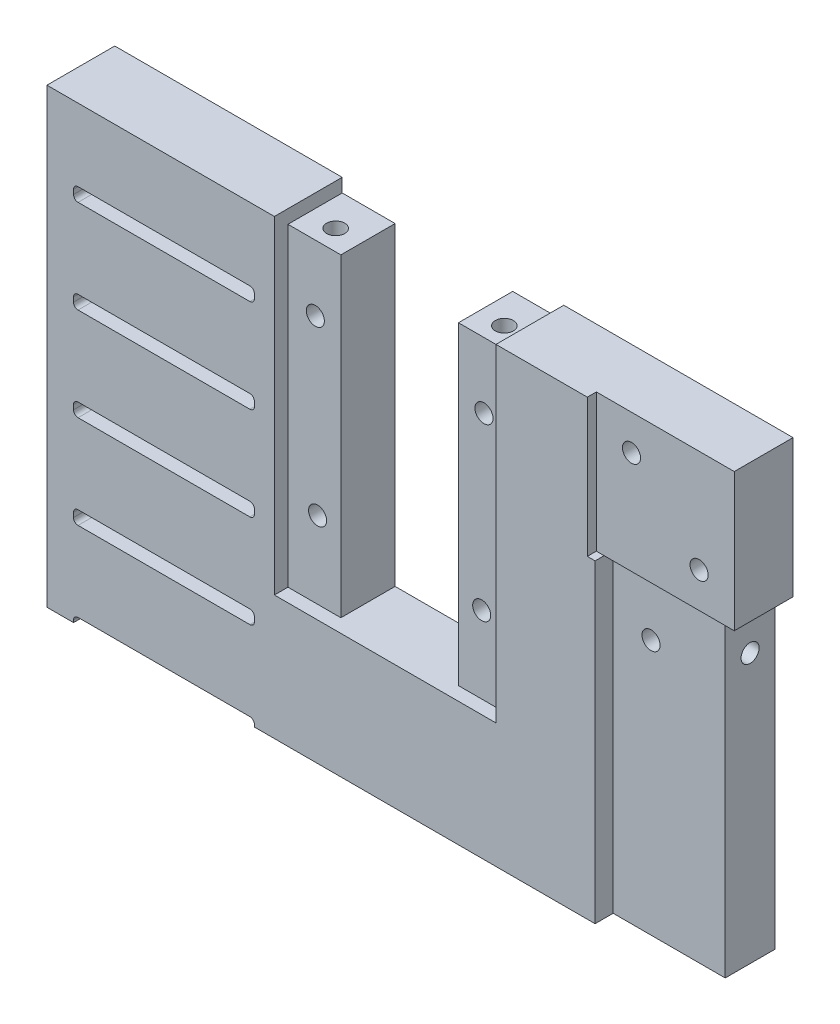
SolidWorks part; units mm, degrees
ref_plane "Alzado" through (0, 0, 0) normal (0, 0, 1) x (1, 0, 0)
ref_plane "Planta" through (0, 0, 0) normal (0, 1, 0) x (1, 0, 0)
ref_plane "Vista lateral" through (0, 0, 0) normal (1, 0, 0) x (0, 0, -1)
sketch "Croquis1" plane through (0, 0, 0) normal (0, 0, 1) x (1, 0, 0)
  line L1 (150, 100) -> (-150, 100)
  line L2 (150, 100) -> (150, -100)
  line L3 (150, -100) -> (-150, -100)
  line L4 (-150, 100) -> (-150, -100)
  line L5 (150, 100) -> (-150, -100) construction
  line L6 (150, -100) -> (-150, 100) construction
  point P0 (0, 0)
  dimension "D1" = 300
  dimension "D2" = 200
extrude "Saliente-Extruir1" add sketch "Croquis1" along normal blind 15
sketch "Croquis2" plane through (0, 0, 15) normal (0, 0, 1) x (1, 0, 0)
  line L0 (0, 0) -> (0, 100) construction
  line L1 (-150, 100) -> (-119.5, 100)
  line L2 (-150, 100) -> (-150, 69.5)
  line L3 (-150, 69.5) -> (-119.5, 69.5)
  line L4 (-119.5, 100) -> (-119.5, 69.5)
  line L5 (150, 100) -> (-150, 100) construction
  line L6 (0, 0) -> (150, 0) construction
  line L7 (150, -100) -> (150, 100) construction
  line L8 (150, 69.5) -> (119.5, 69.5)
  line L9 (119.5, 100) -> (119.5, 69.5)
  line L10 (150, 100) -> (119.5, 100)
  line L11 (150, 100) -> (150, 69.5)
  line L12 (150, -100) -> (150, -69.5)
  line L13 (150, -100) -> (119.5, -100)
  line L14 (119.5, -100) -> (119.5, -69.5)
  line L15 (150, -69.5) -> (119.5, -69.5)
  line L16 (-150, -69.5) -> (-119.5, -69.5)
  line L17 (-119.5, -100) -> (-119.5, -69.5)
  line L18 (-150, -100) -> (-119.5, -100)
  line L19 (-150, -100) -> (-150, -69.5)
  dimension "D1" = 30.5
extrude "Huecos columna" cut sketch "Croquis2" against normal blind 2
sketch "Croquis3" plane through (0, 0, 15) normal (0, 0, 1) x (1, 0, 0)
  line L0 (-119.5, -100) -> (119.5, -100) construction
  line L2 (-88, -97) -> (-88, -27.5)
  line L3 (-88, -27.5) -> (-62, -27.5)
  line L4 (-62, -97) -> (-62, -27.5)
  line L5 (0, 0) -> (0, -100) construction
  line L6 (0, 0) -> (-150, 0) construction
  line L7 (-150, 69.5) -> (-150, -69.5) construction
  line L8 (-88, -58.2044) -> (-150, -58.2044) construction
  line L9 (-62, -60.8904) -> (0, -60.8904) construction
  line L10 (88, -27.5) -> (62, -27.5)
  line L11 (62, -97) -> (62, -27.5)
  line L13 (88, -97) -> (88, -27.5)
  line L14 (88, 97) -> (88, 27.5)
  line L16 (62, 97) -> (62, 27.5)
  line L17 (88, 27.5) -> (62, 27.5)
  line L18 (-88, 27.5) -> (-62, 27.5)
  line L19 (-62, 97) -> (-62, 27.5)
  line L21 (-88, 97) -> (-88, 27.5)
  line L22 (-99.2954, -100) -> (-50.2954, -100)
  line L24 (-99.2954, -100) -> (-99.2954, -97)
  line L25 (-99.2954, -97) -> (-88, -97)
  line L26 (-50.2954, -100) -> (-50.2954, -97)
  line L27 (99.2954, -100) -> (50.2954, -100)
  line L28 (50.2954, -100) -> (50.2954, -97)
  line L29 (99.2954, -97) -> (88, -97)
  line L30 (99.2954, -100) -> (99.2954, -97)
  line L31 (99.2954, 100) -> (99.2954, 97)
  line L32 (99.2954, 97) -> (88, 97)
  line L33 (50.2954, 100) -> (50.2954, 97)
  line L34 (99.2954, 100) -> (50.2954, 100)
  line L35 (-99.2954, 100) -> (-50.2954, 100)
  line L36 (-50.2954, 100) -> (-50.2954, 97)
  line L37 (-99.2954, 97) -> (-88, 97)
  line L38 (-99.2954, 100) -> (-99.2954, 97)
  line L39 (-62, -97) -> (-50.2954, -97)
  line L40 (62, -97) -> (50.2954, -97)
  line L41 (62, 97) -> (50.2954, 97)
  line L42 (-62, 97) -> (-50.2954, 97)
  point P28 (-75, -100)
  point P36 (-74.7954, -100)
  dimension "D1" = 26
  dimension "D2" = 49
  dimension "D3" = 3
  dimension "D4" = 69.5
extrude "huecos  motor" cut sketch "Croquis3" against normal through all
sketch "Croquis4" plane through (0, -97, 0) normal (0, -1, 0) x (1, 0, 0)
  line L0 (-99.2954, 15) -> (-88, 0) construction
  line L1 (-88, 0) -> (-88, 15) construction
  line L2 (-88, 15) -> (-99.2954, 0) construction
  line L3 (0, 0) -> (0, 15) construction
  line L4 (-50.2954, 15) -> (50.2954, 15) construction
  line L5 (-75, 15) -> (-75, 0) construction
  line L6 (-62, 15) -> (-88, 15) construction
  line L7 (-62, 0) -> (-88, 0) construction
  circle A0 centre (-93.6477, 7.5) radius 2
  circle A1 centre (-56.3523, 7.5) radius 2
  circle A2 centre (56.3523, 7.5) radius 2
  circle A3 centre (93.6477, 7.5) radius 2
extrude "side_screws 1" cut sketch "Croquis4" against normal blind 15
sketch "Croquis5" plane through (0, 97, 0) normal (0, 1, 0) x (1, 0, 0)
  line L0 (-99.2954, 0) -> (-88, -15) construction
  line L1 (-88, -15) -> (-88, 0) construction
  line L2 (-88, 0) -> (-99.2954, -15) construction
  line L3 (-75, 0) -> (-75, -15) construction
  line L4 (-88, 0) -> (-62, 0) construction
  line L5 (-88, -15) -> (-62, -15) construction
  line L6 (0, 0) -> (0, -15) construction
  line L7 (50.2954, -15) -> (-50.2954, -15) construction
  circle A0 centre (-93.6477, -7.5) radius 2
  circle A1 centre (-56.3523, -7.5) radius 2
  circle A2 centre (56.3523, -7.5) radius 2
  circle A3 centre (93.6477, -7.5) radius 2
extrude "side screws 2" cut sketch "Croquis5" against normal blind 15
sketch "Croquis7" plane through (0, 0, 15) normal (0, 0, 1) x (1, 0, 0)
  line L0 (-150, -69.5) -> (-119.5, -100) construction
  line L1 (-150, -100) -> (-119.5, -69.5) construction
  line L2 (-150, 0) -> (0, 0) construction
  line L3 (-150, 69.5) -> (-150, -69.5) construction
  line L4 (0, 0) -> (0, -100) construction
  line L5 (-50.2954, -100) -> (50.2954, -100) construction
  line L6 (6.8759, 84) -> (44.8759, 84)
  line L7 (-44.236, 81) -> (-6.236, 81)
  line L8 (-45.236, 82) -> (-45.236, 83)
  line L9 (-44.236, 84) -> (-6.236, 84)
  line L10 (-5.236, 82) -> (-5.236, 83)
  line L11 (-45.236, 81) -> (-5.236, 84) construction
  line L12 (-45.236, 84) -> (-5.236, 81) construction
  line L13 (6.8759, 81) -> (44.8759, 81)
  line L14 (5.8759, 82) -> (5.8759, 83)
  line L15 (45.8759, 82) -> (45.8759, 83)
  line L16 (6.8759, 63.375) -> (44.8759, 63.375)
  line L17 (6.8759, 60.375) -> (44.8759, 60.375)
  line L18 (5.8759, 61.375) -> (5.8759, 62.375)
  line L19 (45.8759, 61.375) -> (45.8759, 62.375)
  line L20 (6.8759, 42.75) -> (44.8759, 42.75)
  line L21 (6.8759, 39.75) -> (44.8759, 39.75)
  line L22 (5.8759, 40.75) -> (5.8759, 41.75)
  line L23 (45.8759, 40.75) -> (45.8759, 41.75)
  line L24 (6.8759, 22.125) -> (44.8759, 22.125)
  line L25 (6.8759, 19.125) -> (44.8759, 19.125)
  line L26 (5.8759, 20.125) -> (5.8759, 21.125)
  line L27 (45.8759, 20.125) -> (45.8759, 21.125)
  line L28 (6.8759, 1.5) -> (44.8759, 1.5)
  line L29 (6.8759, -1.5) -> (44.8759, -1.5)
  line L30 (5.8759, -0.5) -> (5.8759, 0.5)
  line L31 (45.8759, -0.5) -> (45.8759, 0.5)
  line L32 (6.8759, -19.125) -> (44.8759, -19.125)
  line L33 (6.8759, -22.125) -> (44.8759, -22.125)
  line L34 (5.8759, -21.125) -> (5.8759, -20.125)
  line L35 (45.8759, -21.125) -> (45.8759, -20.125)
  line L36 (6.8759, -39.75) -> (44.8759, -39.75)
  line L37 (6.8759, -42.75) -> (44.8759, -42.75)
  line L38 (5.8759, -41.75) -> (5.8759, -40.75)
  line L39 (45.8759, -41.75) -> (45.8759, -40.75)
  line L40 (6.8759, -60.375) -> (44.8759, -60.375)
  line L41 (6.8759, -63.375) -> (44.8759, -63.375)
  line L42 (5.8759, -62.375) -> (5.8759, -61.375)
  line L43 (45.8759, -62.375) -> (45.8759, -61.375)
  line L44 (6.8759, -81) -> (44.8759, -81)
  line L45 (6.8759, -84) -> (44.8759, -84)
  line L46 (5.8759, -83) -> (5.8759, -82)
  line L47 (45.8759, -83) -> (45.8759, -82)
  line L48 (-44.236, 63.375) -> (-6.236, 63.375)
  line L49 (-44.236, 60.375) -> (-6.236, 60.375)
  line L50 (-45.236, 61.375) -> (-45.236, 62.375)
  line L51 (-5.236, 61.375) -> (-5.236, 62.375)
  line L52 (-44.236, 42.75) -> (-6.236, 42.75)
  line L53 (-44.236, 39.75) -> (-6.236, 39.75)
  line L54 (-45.236, 40.75) -> (-45.236, 41.75)
  line L55 (-5.236, 40.75) -> (-5.236, 41.75)
  line L56 (-44.236, 22.125) -> (-6.236, 22.125)
  line L57 (-44.236, 19.125) -> (-6.236, 19.125)
  line L58 (-45.236, 20.125) -> (-45.236, 21.125)
  line L59 (-5.236, 20.125) -> (-5.236, 21.125)
  line L60 (-44.236, 1.5) -> (-6.236, 1.5)
  line L61 (-44.236, -1.5) -> (-6.236, -1.5)
  line L62 (-45.236, -0.5) -> (-45.236, 0.5)
  line L63 (-5.236, -0.5) -> (-5.236, 0.5)
  line L64 (-44.236, -19.125) -> (-6.236, -19.125)
  line L65 (-44.236, -22.125) -> (-6.236, -22.125)
  line L66 (-45.236, -21.125) -> (-45.236, -20.125)
  line L67 (-5.236, -21.125) -> (-5.236, -20.125)
  line L68 (-44.236, -39.75) -> (-6.236, -39.75)
  line L69 (-44.236, -42.75) -> (-6.236, -42.75)
  line L70 (-45.236, -41.75) -> (-45.236, -40.75)
  line L71 (-5.236, -41.75) -> (-5.236, -40.75)
  line L72 (-44.236, -60.375) -> (-6.236, -60.375)
  line L73 (-44.236, -63.375) -> (-6.236, -63.375)
  line L74 (-45.236, -62.375) -> (-45.236, -61.375)
  line L75 (-5.236, -62.375) -> (-5.236, -61.375)
  line L76 (-44.236, -81) -> (-6.236, -81)
  line L77 (-44.236, -84) -> (-6.236, -84)
  line L78 (-45.236, -83) -> (-45.236, -82)
  line L79 (-5.236, -83) -> (-5.236, -82)
  line L80 (39.4634, 84) -> (39.4634, 100) construction
  line L81 (50.2954, 100) -> (-50.2954, 100) construction
  line L82 (-93.6477, -97) -> (-93.6477, -82.5) construction
  line L83 (25.8759, -84) -> (25.8759, -100) construction
  line L84 (-45.236, 82.5) -> (-56.3523, 82.5) construction
  line L85 (-5.236, 82.8086) -> (5.8759, 82.5) construction
  line L87 (45.8759, 82.5) -> (62, 82.5) construction
  line L88 (62, 97) -> (62, 27.5) construction
  line L89 (-88, -97) -> (-99.2954, -97) construction
  line L90 (-75, -27.5) -> (-75, -100) construction
  line L91 (-62, -27.5) -> (-88, -27.5) construction
  line L92 (-56.3523, -97) -> (-56.3523, -82.5) construction
  line L93 (56.3523, -97) -> (56.3523, -82.5) construction
  line L94 (93.6477, -97) -> (93.6477, -82.5) construction
  line L95 (93.6477, 97) -> (93.6477, 82.5) construction
  line L96 (56.3523, 97) -> (56.3523, 82.5) construction
  line L97 (-56.3523, 97) -> (-56.3523, 82.5) construction
  line L98 (-93.6477, 97) -> (-93.6477, 82.5) construction
  circle A0 centre (-127.2782, -92.2218) radius 2
  circle A1 centre (-142.2218, -77.2782) radius 2
  circle A2 centre (-127.2782, 92.2218) radius 2
  circle A3 centre (-142.2218, 77.2782) radius 2
  circle A4 centre (127.2782, -92.2218) radius 2
  circle A5 centre (142.2218, -77.2782) radius 2
  circle A6 centre (127.2782, 92.2218) radius 2
  circle A7 centre (142.2218, 77.2782) radius 2
  arc A8 (-5.236, 82) -> (-6.236, 81) centre (-6.236, 82) cw
  arc A9 (-5.236, 83) -> (-6.236, 84) centre (-6.236, 83) ccw
  arc A10 (-44.236, 81) -> (-45.236, 82) centre (-44.236, 82) cw
  arc A11 (-45.236, 83) -> (-44.236, 84) centre (-44.236, 83) cw
  arc A12 (5.8759, 83) -> (6.8759, 84) centre (6.8759, 83) cw
  arc A13 (6.8759, 81) -> (5.8759, 82) centre (6.8759, 82) cw
  arc A14 (45.8759, 83) -> (44.8759, 84) centre (44.8759, 83) ccw
  arc A15 (45.8759, 82) -> (44.8759, 81) centre (44.8759, 82) cw
  arc A16 (5.8759, 62.375) -> (6.8759, 63.375) centre (6.8759, 62.375) cw
  arc A17 (6.8759, 60.375) -> (5.8759, 61.375) centre (6.8759, 61.375) cw
  arc A18 (45.8759, 62.375) -> (44.8759, 63.375) centre (44.8759, 62.375) ccw
  arc A19 (45.8759, 61.375) -> (44.8759, 60.375) centre (44.8759, 61.375) cw
  arc A20 (5.8759, 41.75) -> (6.8759, 42.75) centre (6.8759, 41.75) cw
  arc A21 (6.8759, 39.75) -> (5.8759, 40.75) centre (6.8759, 40.75) cw
  arc A22 (45.8759, 41.75) -> (44.8759, 42.75) centre (44.8759, 41.75) ccw
  arc A23 (45.8759, 40.75) -> (44.8759, 39.75) centre (44.8759, 40.75) cw
  arc A24 (5.8759, 21.125) -> (6.8759, 22.125) centre (6.8759, 21.125) cw
  arc A25 (6.8759, 19.125) -> (5.8759, 20.125) centre (6.8759, 20.125) cw
  arc A26 (45.8759, 21.125) -> (44.8759, 22.125) centre (44.8759, 21.125) ccw
  arc A27 (45.8759, 20.125) -> (44.8759, 19.125) centre (44.8759, 20.125) cw
  arc A28 (5.8759, 0.5) -> (6.8759, 1.5) centre (6.8759, 0.5) cw
  arc A29 (6.8759, -1.5) -> (5.8759, -0.5) centre (6.8759, -0.5) cw
  arc A30 (45.8759, 0.5) -> (44.8759, 1.5) centre (44.8759, 0.5) ccw
  arc A31 (45.8759, -0.5) -> (44.8759, -1.5) centre (44.8759, -0.5) cw
  arc A32 (5.8759, -20.125) -> (6.8759, -19.125) centre (6.8759, -20.125) cw
  arc A33 (6.8759, -22.125) -> (5.8759, -21.125) centre (6.8759, -21.125) cw
  arc A34 (45.8759, -20.125) -> (44.8759, -19.125) centre (44.8759, -20.125) ccw
  arc A35 (45.8759, -21.125) -> (44.8759, -22.125) centre (44.8759, -21.125) cw
  arc A36 (5.8759, -40.75) -> (6.8759, -39.75) centre (6.8759, -40.75) cw
  arc A37 (6.8759, -42.75) -> (5.8759, -41.75) centre (6.8759, -41.75) cw
  arc A38 (45.8759, -40.75) -> (44.8759, -39.75) centre (44.8759, -40.75) ccw
  arc A39 (45.8759, -41.75) -> (44.8759, -42.75) centre (44.8759, -41.75) cw
  arc A40 (5.8759, -61.375) -> (6.8759, -60.375) centre (6.8759, -61.375) cw
  arc A41 (6.8759, -63.375) -> (5.8759, -62.375) centre (6.8759, -62.375) cw
  arc A42 (45.8759, -61.375) -> (44.8759, -60.375) centre (44.8759, -61.375) ccw
  arc A43 (45.8759, -62.375) -> (44.8759, -63.375) centre (44.8759, -62.375) cw
  arc A44 (5.8759, -82) -> (6.8759, -81) centre (6.8759, -82) cw
  arc A45 (6.8759, -84) -> (5.8759, -83) centre (6.8759, -83) cw
  arc A46 (45.8759, -82) -> (44.8759, -81) centre (44.8759, -82) ccw
  arc A47 (45.8759, -83) -> (44.8759, -84) centre (44.8759, -83) cw
  arc A48 (-45.236, 62.375) -> (-44.236, 63.375) centre (-44.236, 62.375) cw
  arc A49 (-44.236, 60.375) -> (-45.236, 61.375) centre (-44.236, 61.375) cw
  arc A50 (-5.236, 62.375) -> (-6.236, 63.375) centre (-6.236, 62.375) ccw
  arc A51 (-5.236, 61.375) -> (-6.236, 60.375) centre (-6.236, 61.375) cw
  arc A52 (-45.236, 41.75) -> (-44.236, 42.75) centre (-44.236, 41.75) cw
  arc A53 (-44.236, 39.75) -> (-45.236, 40.75) centre (-44.236, 40.75) cw
  arc A54 (-5.236, 41.75) -> (-6.236, 42.75) centre (-6.236, 41.75) ccw
  arc A55 (-5.236, 40.75) -> (-6.236, 39.75) centre (-6.236, 40.75) cw
  arc A56 (-45.236, 21.125) -> (-44.236, 22.125) centre (-44.236, 21.125) cw
  arc A57 (-44.236, 19.125) -> (-45.236, 20.125) centre (-44.236, 20.125) cw
  arc A58 (-5.236, 21.125) -> (-6.236, 22.125) centre (-6.236, 21.125) ccw
  arc A59 (-5.236, 20.125) -> (-6.236, 19.125) centre (-6.236, 20.125) cw
  arc A60 (-45.236, 0.5) -> (-44.236, 1.5) centre (-44.236, 0.5) cw
  arc A61 (-44.236, -1.5) -> (-45.236, -0.5) centre (-44.236, -0.5) cw
  arc A62 (-5.236, 0.5) -> (-6.236, 1.5) centre (-6.236, 0.5) ccw
  arc A63 (-5.236, -0.5) -> (-6.236, -1.5) centre (-6.236, -0.5) cw
  arc A64 (-45.236, -20.125) -> (-44.236, -19.125) centre (-44.236, -20.125) cw
  arc A65 (-44.236, -22.125) -> (-45.236, -21.125) centre (-44.236, -21.125) cw
  arc A66 (-5.236, -20.125) -> (-6.236, -19.125) centre (-6.236, -20.125) ccw
  arc A67 (-5.236, -21.125) -> (-6.236, -22.125) centre (-6.236, -21.125) cw
  arc A68 (-45.236, -40.75) -> (-44.236, -39.75) centre (-44.236, -40.75) cw
  arc A69 (-44.236, -42.75) -> (-45.236, -41.75) centre (-44.236, -41.75) cw
  arc A70 (-5.236, -40.75) -> (-6.236, -39.75) centre (-6.236, -40.75) ccw
  arc A71 (-5.236, -41.75) -> (-6.236, -42.75) centre (-6.236, -41.75) cw
  arc A72 (-45.236, -61.375) -> (-44.236, -60.375) centre (-44.236, -61.375) cw
  arc A73 (-44.236, -63.375) -> (-45.236, -62.375) centre (-44.236, -62.375) cw
  arc A74 (-5.236, -61.375) -> (-6.236, -60.375) centre (-6.236, -61.375) ccw
  arc A75 (-5.236, -62.375) -> (-6.236, -63.375) centre (-6.236, -62.375) cw
  arc A76 (-45.236, -82) -> (-44.236, -81) centre (-44.236, -82) cw
  arc A77 (-44.236, -84) -> (-45.236, -83) centre (-44.236, -83) cw
  arc A78 (-5.236, -82) -> (-6.236, -81) centre (-6.236, -82) ccw
  arc A79 (-5.236, -83) -> (-6.236, -84) centre (-6.236, -83) cw
  circle A80 centre (-93.6477, -82.5) radius 2
  circle A81 centre (-93.1477, -44.5033) radius 2
  circle A82 centre (-56.3523, -82.5) radius 2
  circle A83 centre (-56.8523, -44.5033) radius 2
  circle A84 centre (56.8523, -44.5033) radius 2
  circle A85 centre (56.3523, -82.5) radius 2
  circle A86 centre (93.6477, -82.5) radius 2
  circle A87 centre (93.1477, -44.5033) radius 2
  circle A88 centre (93.6477, 82.5) radius 2
  circle A89 centre (93.1477, 44.5033) radius 2
  circle A90 centre (56.3523, 82.5) radius 2
  circle A91 centre (56.8523, 44.5033) radius 2
  circle A92 centre (-56.3523, 82.5) radius 2
  circle A93 centre (-56.8523, 44.5033) radius 2
  circle A94 centre (-93.6477, 82.5) radius 2
  circle A95 centre (-93.1477, 44.5033) radius 2
  point P32 (-25.236, 82.5)
  dimension "D1" = 11
  dimension "D4" = 1
  dimension "D8" = 38
  dimension "D2" = 3
  dimension "D3" = 40
  dimension "D7" = 14.5
  dimension "D5" = 2
  dimension "D6" = 9
extrude "screws and venti" cut sketch "Croquis7" against normal blind 15
sketch "Croquis9" plane through (0, 0, 15) normal (0, 0, 1) x (1, 0, 0)
  line L1 (-99.2954, -97) -> (-50.2954, -97)
  line L2 (-99.2954, -97) -> (-99.2954, -27.5)
  line L3 (-99.2954, -27.5) -> (-50.2954, -27.5)
  line L4 (-50.2954, -97) -> (-50.2954, -27.5)
  line L5 (-62, -27.5) -> (-88, -27.5) construction
  line L6 (0, 0) -> (-102.0652, 0) construction
  line L7 (0, 0) -> (0, -97) construction
  line L8 (99.2954, -27.5) -> (50.2954, -27.5)
  line L9 (50.2954, -97) -> (50.2954, -27.5)
  line L10 (99.2954, -97) -> (50.2954, -97)
  line L11 (99.2954, -97) -> (99.2954, -27.5)
  line L12 (99.2954, 97) -> (99.2954, 27.5)
  line L13 (99.2954, 97) -> (50.2954, 97)
  line L14 (50.2954, 97) -> (50.2954, 27.5)
  line L15 (99.2954, 27.5) -> (50.2954, 27.5)
  line L16 (-99.2954, 27.5) -> (-50.2954, 27.5)
  line L17 (-50.2954, 97) -> (-50.2954, 27.5)
  line L18 (-99.2954, 97) -> (-50.2954, 97)
  line L19 (-99.2954, 97) -> (-99.2954, 27.5)
extrude "Cortar-Extruir6" cut sketch "Croquis9" against normal blind 3
sketch "Croquis13" plane through (150, 0, 0) normal (1, 0, 0) x (0, 0, -1)
  line L0 (0, -100) -> (0, 100) construction
  line L1 (-15, 69.5) -> (0, 69.5)
  line L2 (-15, 69.5) -> (-15, -69.5)
  line L3 (-15, -69.5) -> (0, -69.5)
  line L4 (0, 69.5) -> (0, -69.5)
extrude "Cortar-Extruir9" cut sketch "Croquis13" against normal blind 4
sketch "Croquis14" plane through (0, 0, 15) normal (0, 0, 1) x (1, 0, 0)
  line L0 (146, -69.5) -> (119.5, -69.5) construction
  line L1 (146, 69.5) -> (121.22, 69.5)
  line L2 (146, 69.5) -> (146, -69.5)
  line L3 (146, -69.5) -> (121.22, -69.5)
  line L4 (121.22, 69.5) -> (121.22, -69.5)
  dimension "D1" = 24.78
extrude "Cortar-Extruir10" cut sketch "Croquis14" against normal blind 4
sketch "Croquis15" plane through (0, 0, 11) normal (0, 0, 1) x (1, 0, 0)
  line L0 (150, -69.5) -> (121.22, -69.5) construction
  line L5 (121.22, 69.5) -> (150, 69.5) construction
  line L6 (121.22, 69.5) -> (121.22, -69.5) construction
  line L7 (129.59, 56.5) -> (129.59, -56.5) construction
  circle A0 centre (129.59, 56.5) radius 2
  circle A1 centre (129.59, -56.5) radius 2
  dimension "D1" = 4
  dimension "D2" = 13
  dimension "D3" = 8.37
  dimension "D4" = 13
extrude "Cortar-Extruir11" cut sketch "Croquis15" against normal blind 4
sketch "Croquis16" plane through (146, 0, 0) normal (1, 0, 0) x (0, 0, -1)
  line L0 (0, -59.5) -> (-5.5, -59.5) construction
  line L1 (0, -69.5) -> (0, 69.5) construction
  line L2 (-5.5, -59.5) -> (-5.5, 59.5) construction
  line L3 (-5.5, 59.5) -> (-5.5, 69.5) construction
  line L6 (0, 69.5) -> (-13, 69.5) construction
  line L7 (-13, -69.5) -> (0, -69.5) construction
  circle A0 centre (-5.5, 59.5) radius 2
  circle A1 centre (-5.5, -59.5) radius 2
  dimension "D2" = 4
  dimension "D1" = 5.5
  dimension "D3" = 10
  dimension "D4" = 10
extrude "side screws - updown" cut sketch "Croquis16" against normal blind 10
sketch "Croquis12" plane through (0, 100, 0) normal (0, 1, 0) x (1, 0, 0)
  line L1 (-150, 0) -> (0, 0)
  line L2 (-150, 0) -> (-150, -15)
  line L3 (-150, -15) -> (0, -15)
  line L4 (0, 0) -> (0, -15)
  point P7 (0, 0)
sketch "Croquis17" plane through (-150, 0, 0) normal (-1, 0, 0) x (0, 0, 1)
  line L1 (0, 0) -> (15, 0)
  line L2 (0, 0) -> (0, -100)
  line L3 (0, -100) -> (15, -100)
  line L4 (15, 0) -> (15, -100)
  point P6 (0, 0)
extrude "Cortar-Extruir14" cut sketch "Croquis12" against normal blind 200
extrude "Cortar-Extruir15" cut sketch "Croquis17" against normal blind 300
sketch "Croquis19" plane through (0, 0, 0) normal (-1, 0, 0) x (0, 0, 1)
  line L0 (15, 100) -> (0, 100) construction
  line L2 (0, 0) -> (15, 0) construction
  circle A0 centre (7.5, 69.08) radius 3.5
  circle A1 centre (7.5, 32.42) radius 3.5
  dimension "D1" = 7
  dimension "D2" = 30.92
  dimension "D3" = 32.42
extrude "Cortar-Extruir16" cut sketch "Croquis19" against normal blind 25
sketch "Croquis20" plane through (0, 0, 0) normal (0, -1, 0) x (1, 0, 0)
  line L0 (45.8759, 7.5) -> (79.2506, 7.5) construction
  line L1 (45.8759, 0) -> (45.8759, 15) construction
  line L2 (79.2506, 7.5) -> (112.6253, 7.5) construction
  line L3 (112.6253, 7.5) -> (146, 7.5) construction
  line L4 (146, 0) -> (146, 11) construction
  circle A0 centre (79.2506, 7.5) radius 3.5
  circle A1 centre (112.6253, 7.5) radius 3.5
  dimension "D1" = 7
extrude "Cortar-Extruir17" cut sketch "Croquis20" against normal blind 25
